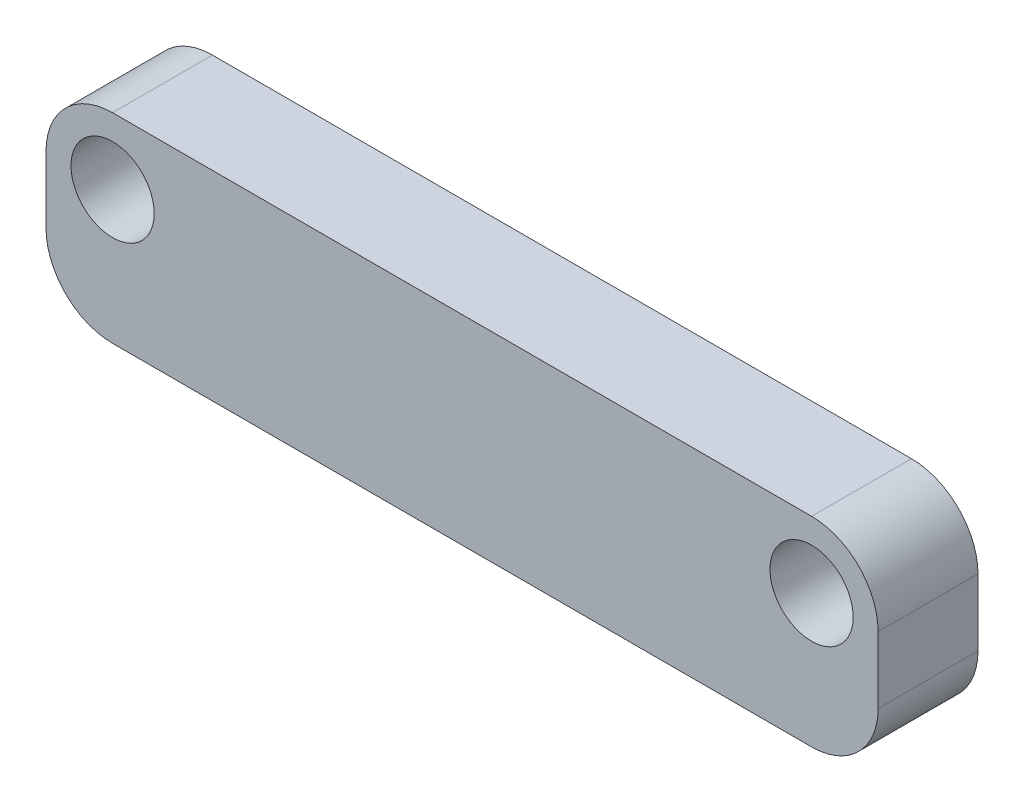
SolidWorks part; units mm, degrees
ref_plane "Front Plane" through (0, 0, 0) normal (0, 0, 1) x (1, 0, 0)
ref_plane "Top Plane" through (0, 0, 0) normal (0, 1, 0) x (1, 0, 0)
ref_plane "Right Plane" through (0, 0, 0) normal (1, 0, 0) x (0, 0, -1)
sketch "Sketch1" plane through (0, 0, 0) normal (0, 0, 1) x (1, 0, 0)
  line L1 (-21, 6) -> (21, 6)
  line L2 (-25, 2) -> (-25, -2)
  line L3 (-21, -6) -> (21, -6)
  line L4 (25, 2) -> (25, -2)
  line L5 (-25, 6) -> (25, -6) construction
  line L6 (-25, -6) -> (25, 6) construction
  arc A0 (21, -6) -> (25, -2) centre (21, -2) ccw
  arc A1 (-25, -2) -> (-21, -6) centre (-21, -2) ccw
  arc A2 (21, 6) -> (25, 2) centre (21, 2) cw
  arc A3 (-21, 6) -> (-25, 2) centre (-21, 2) ccw
  circle A4 centre (-21, 2) radius 2.5
  circle A5 centre (21, 2) radius 2.5
  point P0 (0, 0)
  dimension "D3" = 4
  dimension "D1" = 50
  dimension "D2" = 12
extrude "Boss-Extrude3" add sketch "Sketch1" along normal blind 6
